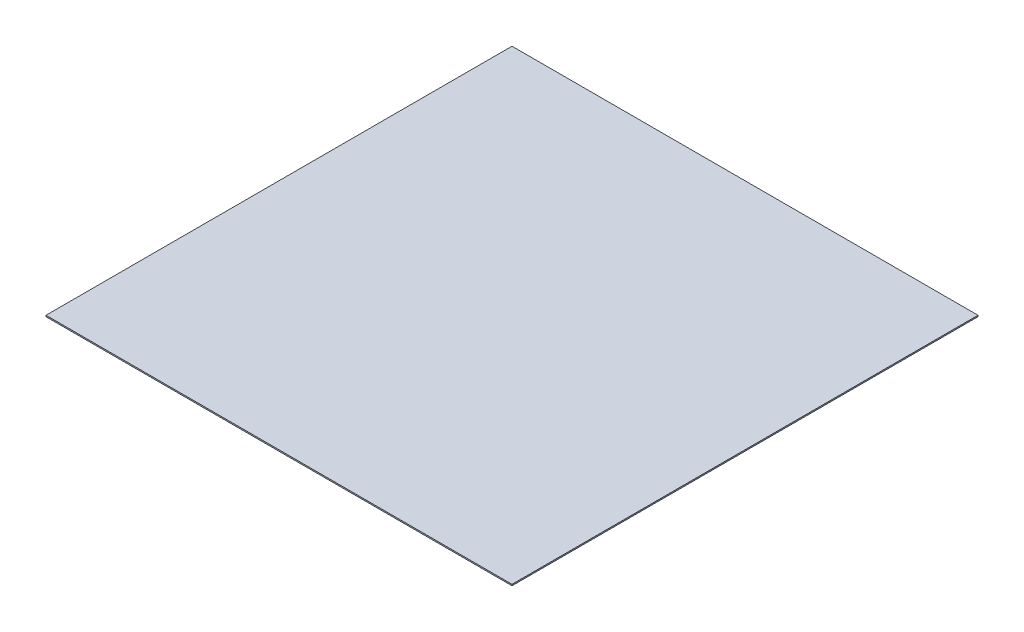
SolidWorks part; units mm, degrees
ref_plane "Alzado" through (0, 0, 0) normal (0, 0, 1) x (1, 0, 0)
ref_plane "Planta" through (0, 0, 0) normal (0, 1, 0) x (1, 0, 0)
ref_plane "Vista lateral" through (0, 0, 0) normal (1, 0, 0) x (0, 0, -1)
sketch "Croquis1" plane through (0, 0, 0) normal (0, 1, 0) x (1, 0, 0)
  line L1 (0, 0) -> (25, 0)
  line L2 (0, 0) -> (0, 25)
  line L3 (0, 25) -> (25, 25)
  line L4 (25, 0) -> (25, 25)
  dimension "D1" = 25
extrude "Saliente-Extruir1" add sketch "Croquis1" along normal blind 0.07
